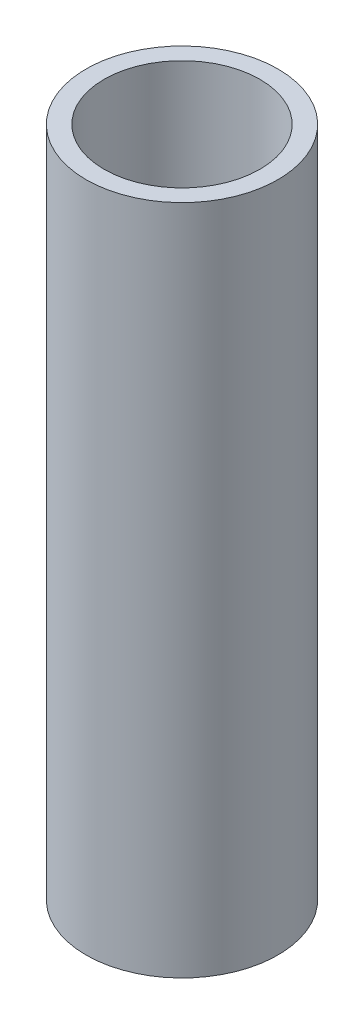
SolidWorks part; units mm, degrees
ref_plane "Płaszczyzna przednia" through (0, 0, 0) normal (0, 0, 1) x (1, 0, 0)
ref_plane "Płaszczyzna górna" through (0, 0, 0) normal (0, 1, 0) x (1, 0, 0)
ref_plane "Płaszczyzna prawa" through (0, 0, 0) normal (1, 0, 0) x (0, 0, -1)
sketch "Sketch1" plane through (0, 0, 0) normal (0, 1, 0) x (1, 0, 0)
  circle A0 centre (0, 0) radius 3.25
  circle A1 centre (0, 0) radius 4
  dimension "D1" = 6.5
  dimension "D2" = 8
extrude "Boss-Extrude1" add sketch "Sketch1" along normal blind 28
